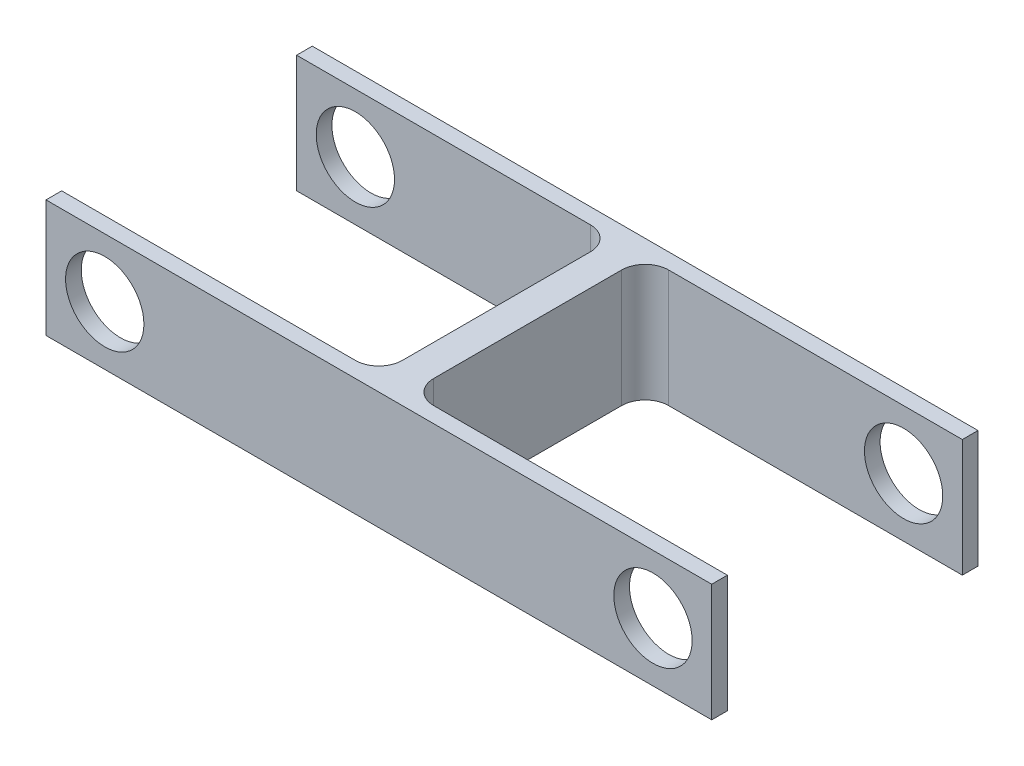
SolidWorks part; units mm, degrees
ref_plane "Front Plane" through (0, 0, 0) normal (0, 0, 1) x (1, 0, 0)
ref_plane "Top Plane" through (0, 0, 0) normal (0, 1, 0) x (1, 0, 0)
ref_plane "Right Plane" through (0, 0, 0) normal (1, 0, 0) x (0, 0, -1)
sketch "Sketch1" plane through (0, 0, 0) normal (0, 0, 1) x (1, 0, 0)
  line L1 (-107.95, -19.05) -> (107.95, -19.05)
  line L2 (-107.95, -19.05) -> (-107.95, 19.05)
  line L3 (-107.95, 19.05) -> (107.95, 19.05)
  line L4 (107.95, -19.05) -> (107.95, 19.05)
  line L5 (-107.95, -19.05) -> (107.95, 19.05) construction
  line L6 (-107.95, 19.05) -> (107.95, -19.05) construction
  point P0 (0, 0)
  dimension "D1" = 38.1
  dimension "D2" = 215.9
extrude "Boss-Extrude1" add sketch "Sketch1" along normal blind 5.08
sketch "Sketch2" plane through (0, 0, 0) normal (0, 0, 1) x (1, 0, 0)
  line L0 (-107.95, 0) -> (107.95, 0) construction
  line L1 (-107.95, 19.05) -> (-107.95, -19.05) construction
  line L2 (107.95, -19.05) -> (107.95, 19.05) construction
  line L3 (0, 0) -> (0, 19.05) construction
  line L4 (107.95, 19.05) -> (-107.95, 19.05) construction
  circle A0 centre (-88.9, 0) radius 12.7
  circle A1 centre (88.9, 0) radius 12.7
  dimension "D2" = 25.4
  dimension "D1" = 177.8
extrude "Cut-Extrude1" cut sketch "Sketch2" along normal through all
sketch "Sketch3" plane through (0, 0, 0) normal (0, 0, 1) x (1, 0, 0)
  line L0 (107.95, 19.05) -> (-107.95, 19.05) construction
  line L1 (-5.08, -19.05) -> (5.08, -19.05)
  line L2 (-5.08, -19.05) -> (-5.08, 19.05)
  line L3 (-5.08, 19.05) -> (5.08, 19.05)
  line L4 (5.08, -19.05) -> (5.08, 19.05)
  line L5 (-5.08, -19.05) -> (5.08, 19.05) construction
  line L6 (-5.08, 19.05) -> (5.08, -19.05) construction
  point P0 (0, 0)
  dimension "D1" = 10.16
extrude "Boss-Extrude2" add sketch "Sketch3" against normal blind 38.1
ref_plane "Plane1" through (0, 0, -38.1) normal (0, 0, -1) x (-1, 0, 0)
mirror "Mirror2" about plane through (0, 0, -38.1) normal (0, 0, -1) of "Boss-Extrude2", "Cut-Extrude1", "Boss-Extrude1"
mirror "Mirror3" about plane through (0, 0, -38.1) normal (0, 0, -1) of "Cut-Extrude1", "Boss-Extrude1"
fillet "Fillet1" radius 7.62 4 edges at (5.08, 0, -76.2) (-5.08, 0, -76.2) (-5.08, 0, 0) (5.08, 0, 0)
